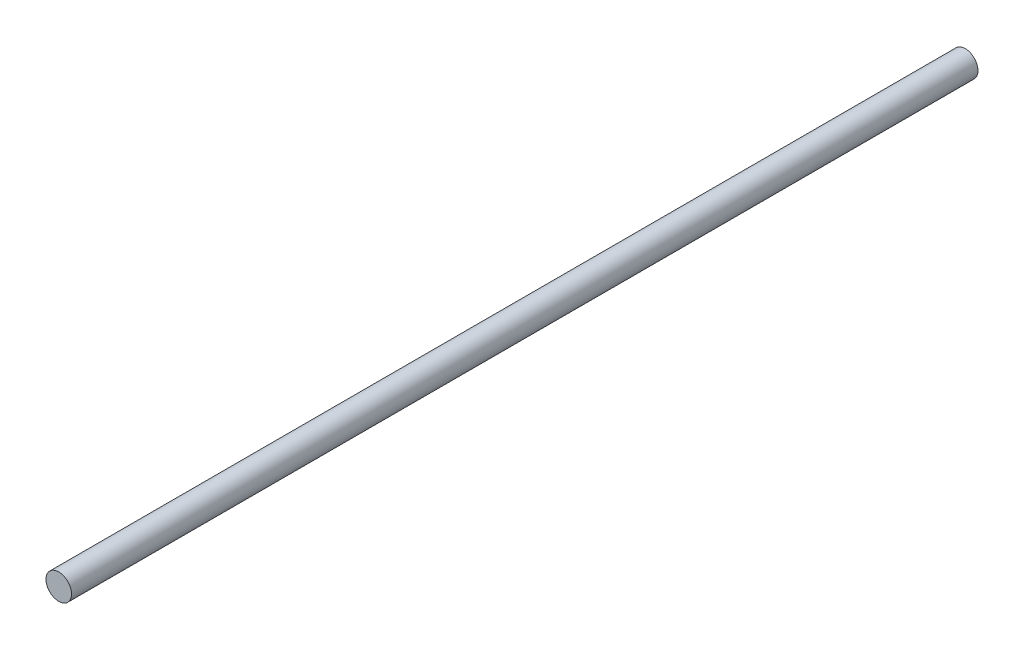
SolidWorks part; units mm, degrees
ref_plane "Front Plane" through (0, 0, 0) normal (0, 0, 1) x (1, 0, 0)
ref_plane "Top Plane" through (0, 0, 0) normal (0, 1, 0) x (1, 0, 0)
ref_plane "Right Plane" through (0, 0, 0) normal (1, 0, 0) x (0, 0, -1)
sketch "Sketch1" plane through (0, 0, 0) normal (0, 0, 1) x (1, 0, 0)
  circle A0 centre (0, 0) radius 3.937
  dimension "D1" = 7.874
extrude "Boss-Extrude1" add sketch "Sketch1" along normal blind 279.4
